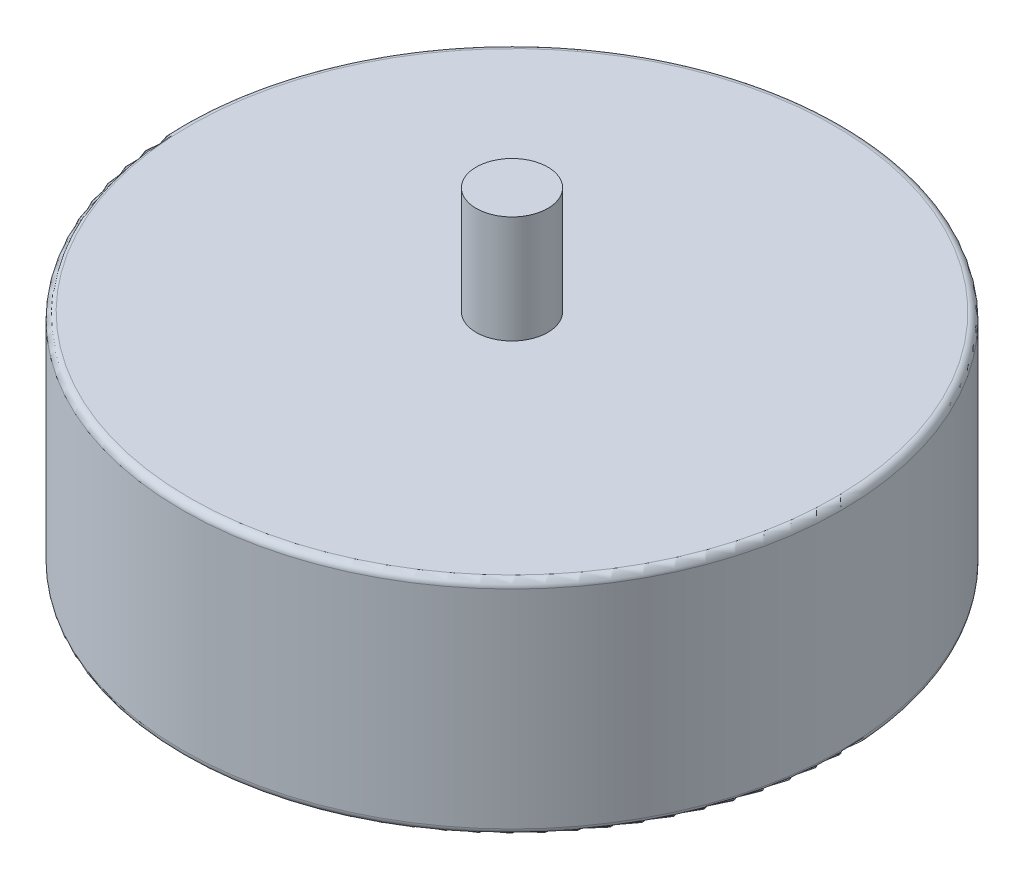
SolidWorks part; units mm, degrees
material "1060 合金"
ref_plane "前视基准面" through (0, 0, 0) normal (0, 0, 1) x (1, 0, 0)
ref_plane "上视基准面" through (0, 0, 0) normal (0, 1, 0) x (1, 0, 0)
ref_plane "右视基准面" through (0, 0, 0) normal (1, 0, 0) x (0, 0, -1)
sketch "草图1" plane through (0, 0, 0) normal (0, 1, 0) x (1, 0, 0)
  circle A0 centre (0, 0) radius 46
extrude "凸台-拉伸1" add sketch "草图1" along normal blind 31
sketch "草图2" plane through (0, 31, 0) normal (0, 1, 0) x (1, 0, 0)
  circle A0 centre (0, 0) radius 5
extrude "凸台-拉伸2" add sketch "草图2" along normal blind 15
fillet "圆角2" radius 1 2 edges at (0, 0, 46) (0, 31, 46)
